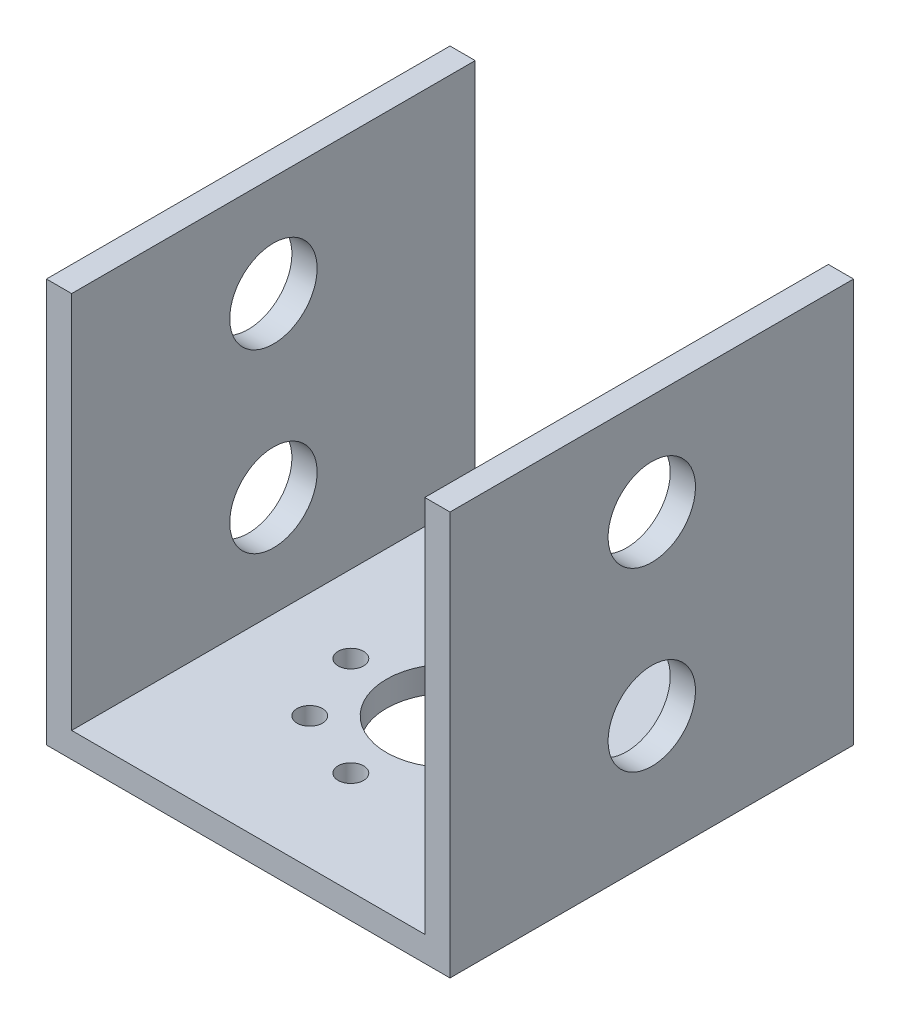
SolidWorks part; units mm, degrees
material "6063-T5"
ref_plane "Front Plane" through (0, 0, 0) normal (0, 0, 1) x (1, 0, 0)
ref_plane "Top Plane" through (0, 0, 0) normal (0, 1, 0) x (1, 0, 0)
ref_plane "Right Plane" through (0, 0, 0) normal (1, 0, 0) x (0, 0, -1)
sketch "Sketch1" plane through (0, 0, 0) normal (0, 0, 1) x (1, 0, 0)
  line L0 (-11.1125, 0) -> (11.1125, 0)
  line L1 (0, 0) -> (0, -1.5875) construction
  line L2 (-12.7, -1.5875) -> (12.7, -1.5875)
  line L3 (12.7, -1.5875) -> (12.7, 23.8125)
  line L4 (-12.7, -1.5875) -> (-12.7, 23.8125)
  line L5 (-11.1125, 0) -> (-11.1125, 23.8125)
  line L6 (-11.1125, 23.8125) -> (-12.7, 23.8125)
  line L7 (11.1125, 0) -> (11.1125, 23.8125)
  line L8 (11.1125, 23.8125) -> (12.7, 23.8125)
  point P3 (0, 0)
  point P9 (0, -1.5875)
  dimension "D1" = 22.225
  dimension "D2" = 1.5875
  dimension "D3" = 25.4
  dimension "D4" = 25.4
extrude "Boss-Extrude1" add sketch "Sketch1" along normal blind 25.4
sketch "Sketch2" plane through (12.7, 0, 0) normal (1, 0, 0) x (0, 0, -1)
  line L0 (-25.4, 23.8125) -> (0, 23.8125) construction
  line L1 (-25.4, -1.5875) -> (-25.4, 23.8125) construction
  line L3 (-25.4, -1.5875) -> (0, -1.5875) construction
  circle A0 centre (-12.7, 17.4625) radius 2.75
  circle A1 centre (-12.7, 6.35) radius 2.75
  point P2 (0, 0)
  point P6 (-12.7, 23.8125)
  dimension "D1" = 5.5
  dimension "D4" = 7.9375
  dimension "D2" = 6.35
  dimension "D3" = 12.7
extrude "Cut-Extrude1" cut sketch "Sketch2" against normal through all
sketch "Sketch3" plane through (0, 0, 0) normal (0, 1, 0) x (1, 0, 0)
  line L0 (-11.1125, 0) -> (11.1125, -25.4) construction
  circle A0 centre (0, -12.7) radius 4
  point P6 (0, -6.4583)
  point P10 (4.4135, -8.2865)
  point P11 (6.2417, -12.7)
  point P12 (4.4135, -17.1135)
  point P13 (0, -18.9417)
  point P14 (-4.4135, -17.1135)
  point P15 (-6.2417, -12.7)
  point P16 (-4.4135, -8.2865)
  point P17 (0, -12.7)
  dimension "D1" = 8
  dimension "D2" = 6.2417
  dimension "D3" = 8
extrude "Cut-Extrude2" cut sketch "Sketch3" against normal through all
hole_wizard "M2x0.4 Tapped Hole1" positions "Sketch4" profile "Sketch5" tap size "M2x0.4" standard "ANSI Metric" end condition through all
sketch "Sketch4" plane through (0, 0, 0) normal (0, 1, 0) x (1, 0, 0)
  point P0 (0, -6.4583)
  point P3 (4.4135, -8.2865)
  point P6 (6.2417, -12.7)
  point P9 (4.4135, -17.1135)
  point P12 (0, -18.9417)
  point P15 (-4.4135, -17.1135)
  point P18 (-6.2417, -12.7)
  point P21 (-4.4135, -8.2865)
sketch "Sketch5" plane through (0, 0, 6.4583) normal (1, 0, 0) x (0, 0, 1)
  line L0 (0, 0) -> (0, 1.5875)
  line L1 (0, 1.5875) -> (0.8, 1.5875)
  line L2 (0.8, 1.5875) -> (0.8, 0)
  line L5 (0.8, 0) -> (0, 0)
  line L11 (0, -6.35) -> (0, 107.95) construction
  dimension "Thru Tap Drill Dia." = 1.6
  dimension "Thru Tap Drill Depth" = 1.5875
cosmetic thread "Hole Thread1" parameters "D2"=2
cosmetic thread "Hole Thread2" parameters "D2"=2
cosmetic thread "Hole Thread3" parameters "D2"=2
cosmetic thread "Hole Thread4" parameters "D2"=2
cosmetic thread "Hole Thread5" parameters "D2"=2
cosmetic thread "Hole Thread6" parameters "D2"=2
cosmetic thread "Hole Thread7" parameters "D2"=2
cosmetic thread "Hole Thread8" parameters "D2"=2
